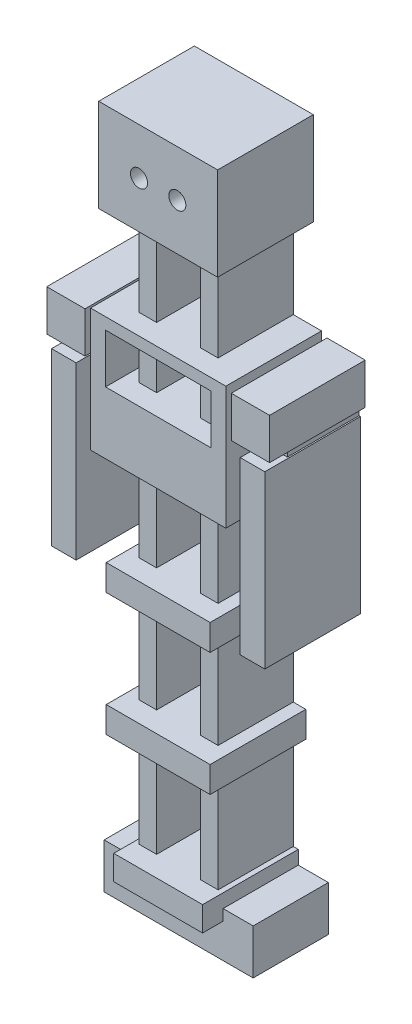
SolidWorks part; units mm, degrees
ref_plane "Front Plane" through (0, 0, 0) normal (0, 0, 1) x (1, 0, 0)
ref_plane "Top Plane" through (0, 0, 0) normal (0, 1, 0) x (1, 0, 0)
ref_plane "Right Plane" through (0, 0, 0) normal (1, 0, 0) x (0, 0, -1)
sketch "Sketch1" plane through (0, 0, 0) normal (0, 0, 1) x (1, 0, 0)
  line L1 (-109, 0) -> (109, 0)
  line L2 (-109, 0) -> (-109, 66)
  line L3 (-109, 66) -> (109, 66)
  line L4 (109, 0) -> (109, 66)
  line L6 (-57.7, 75) -> (-32.3, 75)
  line L7 (-57.7, 75) -> (-57.7, 895)
  line L8 (-57.7, 895) -> (-32.3, 895)
  line L9 (-32.3, 75) -> (-32.3, 895)
  line L11 (32.3, 75) -> (57.7, 75)
  line L12 (32.3, 75) -> (32.3, 895)
  line L13 (32.3, 895) -> (57.7, 895)
  line L14 (57.7, 75) -> (57.7, 895)
extrude "Boss-Extrude1" add sketch "Sketch1" along normal blind 110
sketch "Sketch2" plane through (0, 0, 0) normal (0, 0, 1) x (1, 0, 0)
  line L1 (-65, 50) -> (65, 50)
  line L2 (-65, 50) -> (-65, 86)
  line L3 (-65, 86) -> (65, 86)
  line L4 (65, 50) -> (65, 86)
  line L6 (-76, 231) -> (76, 231)
  line L7 (-76, 231) -> (-76, 269)
  line L8 (-76, 269) -> (76, 269)
  line L9 (76, 231) -> (76, 269)
  line L11 (-76, 411) -> (76, 411)
  line L12 (-76, 411) -> (-76, 449)
  line L13 (-76, 449) -> (76, 449)
  line L14 (76, 411) -> (76, 449)
  line L16 (-99, 580) -> (99, 580)
  line L17 (-99, 580) -> (-99, 760)
  line L18 (-99, 760) -> (99, 760)
  line L19 (99, 580) -> (99, 760)
  line L21 (-77, 671) -> (77, 671)
  line L22 (-77, 671) -> (-77, 743)
  line L23 (-77, 743) -> (77, 743)
  line L24 (77, 671) -> (77, 743)
  line L26 (-163, 695) -> (-107, 695)
  line L27 (-163, 695) -> (-163, 755)
  line L28 (-163, 755) -> (-107, 755)
  line L29 (-107, 695) -> (-107, 755)
  line L31 (107, 695) -> (163, 695)
  line L32 (107, 695) -> (107, 755)
  line L33 (107, 755) -> (163, 755)
  line L34 (163, 695) -> (163, 755)
  line L36 (-156, 430) -> (-120, 430)
  line L37 (-156, 430) -> (-156, 680)
  line L38 (-156, 680) -> (-120, 680)
  line L39 (-120, 430) -> (-120, 680)
  line L41 (120, 430) -> (156, 430)
  line L42 (120, 430) -> (120, 680)
  line L43 (120, 680) -> (156, 680)
  line L44 (156, 430) -> (156, 680)
  line L46 (-87, 892) -> (87, 892)
  line L47 (-87, 892) -> (-87, 1028)
  line L48 (-87, 1028) -> (87, 1028)
  line L49 (87, 892) -> (87, 1028)
  circle A0 centre (-28, 960) radius 12.5
  circle A1 centre (28, 960) radius 12.5
extrude "Boss-Extrude2" add sketch "Sketch2" along normal blind 140
sketch "Sketch3" plane through (0, 0, 0) normal (0, 0, 1) x (1, 0, 0)
  line L1 (-115, 703) -> (-91, 703)
  line L2 (-115, 703) -> (-115, 747)
  line L3 (-115, 747) -> (-91, 747)
  line L4 (-91, 703) -> (-91, 747)
  line L6 (91, 703) -> (115, 703)
  line L7 (91, 703) -> (91, 747)
  line L8 (91, 747) -> (115, 747)
  line L9 (115, 703) -> (115, 747)
  line L11 (-154, 673) -> (-122, 673)
  line L12 (-154, 673) -> (-154, 703)
  line L13 (-154, 703) -> (-122, 703)
  line L14 (-122, 673) -> (-122, 703)
  line L16 (122, 673) -> (154, 673)
  line L17 (122, 673) -> (122, 703)
  line L18 (122, 703) -> (154, 703)
  line L19 (154, 673) -> (154, 703)
  line L21 (-58, 867) -> (58, 867)
  line L22 (-58, 867) -> (-58, 903)
  line L23 (-58, 903) -> (58, 903)
  line L24 (58, 867) -> (58, 903)
extrude "Boss-Extrude3" add sketch "Sketch3" along normal blind 105
